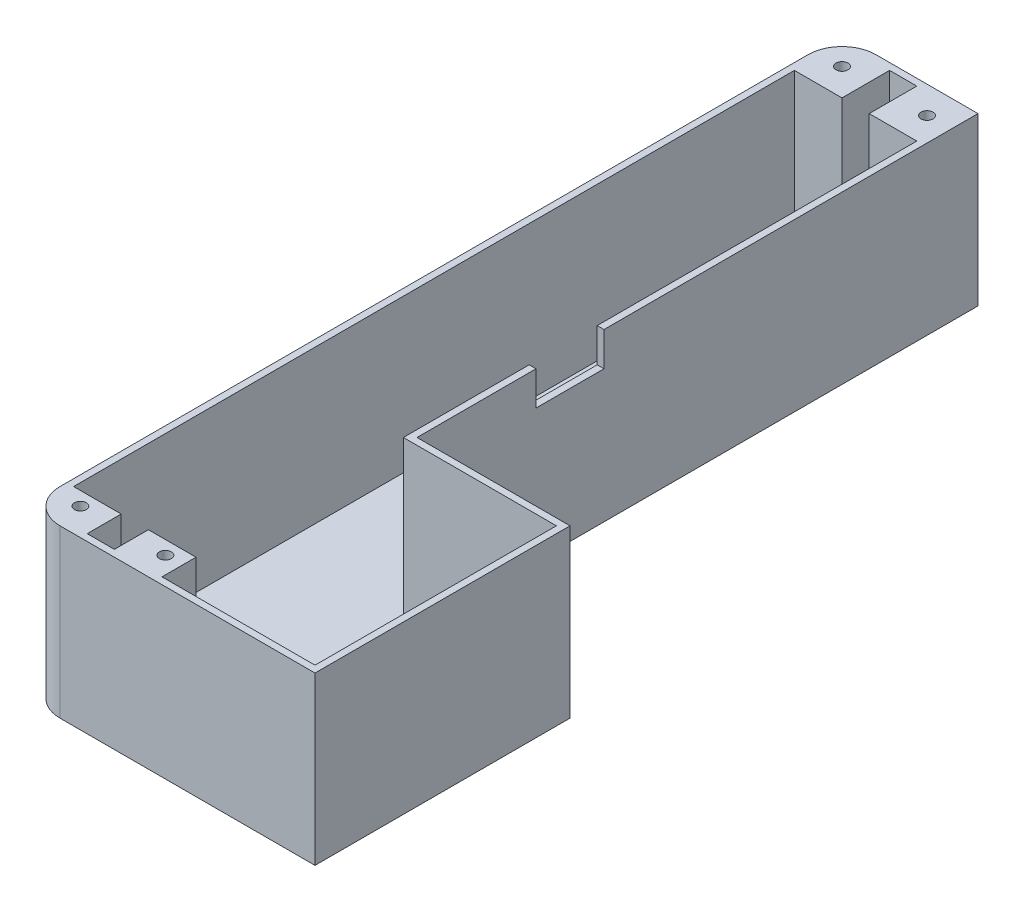
SolidWorks part; units mm, degrees
ref_plane "Front Plane" through (0, 0, 0) normal (0, 0, 1) x (1, 0, 0)
ref_plane "Top Plane" through (0, 0, 0) normal (0, 1, 0) x (1, 0, 0)
ref_plane "Right Plane" through (0, 0, 0) normal (1, 0, 0) x (0, 0, -1)
sketch "Sketch1" plane through (0, 0, 0) normal (0, 1, 0) x (1, 0, 0)
  line L1 (-20, 120) -> (20, 120)
  line L2 (-20, 120) -> (-20, -120)
  line L3 (-20, -120) -> (20, -120)
  line L4 (20, 120) -> (20, -120)
  dimension "D1" = 40
  dimension "D2" = 240
  dimension "D3" = 120
  dimension "D4" = 20
extrude "Boss-Extrude2" add sketch "Sketch1" along normal blind 4
sketch "Sketch2" plane through (0, 4, 0) normal (0, 1, 0) x (1, 0, 0)
  line L1 (20, 120) -> (-20, 120)
  line L2 (20, 120) -> (20, -120)
  line L3 (20, -120) -> (-20, -120)
  line L4 (-20, 120) -> (-20, -120)
  line L6 (18, 118) -> (-18, 118)
  line L7 (18, 118) -> (18, -118)
  line L8 (18, -118) -> (-18, -118)
  line L9 (-18, 118) -> (-18, -118)
  dimension "D1" = 36
  dimension "D2" = 236
  dimension "D3" = 2
  dimension "D4" = 2
extrude "Boss-Extrude4" add sketch "Sketch2" along normal blind 45
sketch "Sketch3" plane through (0, 4, 0) normal (0, 1, 0) x (1, 0, 0)
  line L1 (-18, 118) -> (-4, 118)
  line L2 (-18, 118) -> (-18, 104)
  line L3 (-18, 104) -> (-4, 104)
  line L4 (-4, 118) -> (-4, 104)
  line L5 (18, 118) -> (4, 118)
  line L6 (18, 118) -> (18, 104)
  line L7 (18, 104) -> (4, 104)
  line L8 (4, 118) -> (4, 104)
  line L9 (-18, -118) -> (-4, -118)
  line L10 (-18, -118) -> (-18, -104)
  line L11 (-18, -104) -> (-4, -104)
  line L12 (-4, -118) -> (-4, -104)
  line L13 (18, -118) -> (4, -118)
  line L14 (18, -118) -> (18, -104)
  line L15 (18, -104) -> (4, -104)
  line L16 (4, -118) -> (4, -104)
  dimension "D1" = 14
  dimension "D2" = 14
  dimension "D3" = 14
  dimension "D4" = 14
  dimension "D5" = 14
  dimension "D6" = 14
  dimension "D7" = 14
  dimension "D8" = 14
extrude "Boss-Extrude5" add sketch "Sketch3" along normal blind 45
sketch "Sketch4" plane through (0, 0, 0) normal (0, -1, 0) x (-1, 0, 0)
  line L0 (20, -120) -> (-20, -120) construction
  line L1 (20, 120) -> (20, -120) construction
  line L2 (-20, 120) -> (20, 120) construction
  circle A0 centre (12, -112) radius 1.75
  circle A1 centre (-13, -112) radius 1.75
  circle A2 centre (12, 112) radius 1.75
  circle A3 centre (-13, 112) radius 1.75
  dimension "D1" = 3.5
  dimension "D2" = 3.5
  dimension "D3" = 3.5
  dimension "D4" = 3.5
  dimension "D5" = 8
  dimension "D6" = 8
  dimension "D7" = 8
  dimension "D8" = 25
  dimension "D9" = 8
  dimension "D10" = 25
  dimension "D11" = 8
  dimension "D12" = 8
extrude "Cut-Extrude1" cut sketch "Sketch4" against normal blind 90
fillet "Fillet1" radius 10 1 edges at (-20, 24.5, -120)
fillet "Fillet2" radius 10 1 edges at (-20, 24.5, 120)
sketch "Sketch5" plane through (0, 0, 0) normal (0, -1, 0) x (-1, 0, 0)
  circle A0 centre (12, -112) radius 3.5
  circle A1 centre (-13, -112) radius 3.5
  circle A2 centre (12, 112) radius 3.5
  circle A3 centre (-13, 112) radius 3.5
  dimension "D1" = 7
  dimension "D2" = 7
  dimension "D3" = 7
  dimension "D4" = 7
extrude "Cut-Extrude2" cut sketch "Sketch5" against normal blind 45
sketch "Sketch6" plane through (20, 0, 0) normal (1, 0, 0) x (0, 0, -1)
  line L0 (-120, 49) -> (120, 49) construction
  line L1 (-10, 49) -> (10, 49)
  line L2 (-10, 49) -> (-10, 39)
  line L3 (-10, 39) -> (10, 39)
  line L4 (10, 49) -> (10, 39)
  dimension "D1" = 20
  dimension "D2" = 10
  dimension "D3" = 10
extrude "Cut-Extrude3" cut sketch "Sketch6" against normal blind 10
sketch "Sketch7" plane through (20, 0, 0) normal (1, 0, 0) x (0, 0, -1)
  line L0 (-120, 0) -> (120, 0) construction
  line L1 (-120, 49) -> (-45, 49)
  line L2 (-120, 49) -> (-120, 0)
  line L3 (-120, 0) -> (-45, 0)
  line L4 (-45, 49) -> (-45, 0)
  dimension "D1" = 75
extrude "Boss-Extrude6" add sketch "Sketch7" along normal blind 45
sketch "Sketch8" plane through (0, 49, 0) normal (0, 1, 0) x (1, 0, 0)
  line L0 (18, -104) -> (18, -10) construction
  line L1 (18, -47) -> (63, -47)
  line L2 (18, -47) -> (18, -118)
  line L3 (18, -118) -> (63, -118)
  line L4 (63, -47) -> (63, -118)
  line L6 (65, -45) -> (20, -45) construction
  dimension "D1" = 45
  dimension "D2" = 71
  dimension "D3" = 2
extrude "Cut-Extrude4" cut sketch "Sketch8" against normal blind 45
sketch "Sketch9" plane through (0, 49, 0) normal (0, 1, 0) x (1, 0, 0)
  line L1 (18, -104) -> (-18, -104)
  line L2 (18, -104) -> (18, -108)
  line L3 (18, -108) -> (-18, -108)
  line L4 (-18, -104) -> (-18, -108)
  dimension "D1" = 36
  dimension "D2" = 4
extrude "Cut-Extrude5" cut sketch "Sketch9" against normal blind 50
